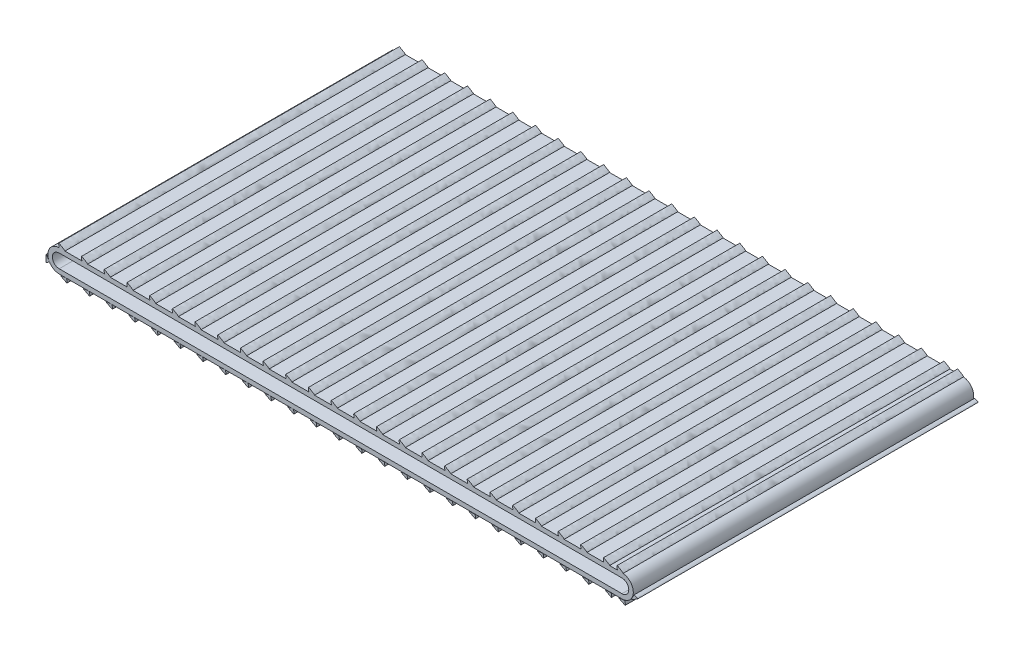
SolidWorks part; units mm, degrees
ref_plane "Front Plane" through (0, 0, 0) normal (0, 0, 1) x (1, 0, 0)
ref_plane "Top Plane" through (0, 0, 0) normal (0, 1, 0) x (1, 0, 0)
ref_plane "Right Plane" through (0, 0, 0) normal (1, 0, 0) x (0, 0, -1)
sketch "Sketch1" plane through (0, 0, 0) normal (0, 0, 1) x (1, 0, 0)
  line L0 (0, 40) -> (1240, 40)
  line L1 (0, 0) -> (1240, 0)
  line L3 (0, 50) -> (1240, 50)
  line L5 (0, 10) -> (1240, 10)
  arc A0 (1240, 50) -> (1240, 0) centre (1240, 25) cw
  arc A1 (0, 50) -> (0, 0) centre (0, 25) ccw
  arc A2 (1240, 40) -> (1240, 10) centre (1240, 25) cw
  arc A3 (0, 40) -> (0, 10) centre (0, 25) ccw
  dimension "D1" = 50
  dimension "D2" = 1240
  dimension "D3" = 10
extrude "Boss-Extrude1" add sketch "Sketch1" along normal blind 750
sketch "Sketch3" plane through (0, 0, 0) normal (0, 0, 1) x (1, 0, 0)
  line L0 (1240, 50) -> (0, 50) construction
  line L1 (7.4471, 50) -> (0, 50)
  line L2 (7.4471, 50) -> (12.5678, 50)
  line L3 (57.4471, 50) -> (62.5678, 50)
  line L4 (57.4471, 50) -> (50, 50)
  line L5 (107.4471, 50) -> (112.5678, 50)
  line L6 (107.4471, 50) -> (100, 50)
  line L7 (157.4471, 50) -> (162.5678, 50)
  line L8 (157.4471, 50) -> (150, 50)
  line L9 (207.4471, 50) -> (212.5678, 50)
  line L10 (207.4471, 50) -> (200, 50)
  line L11 (257.4471, 50) -> (262.5678, 50)
  line L12 (257.4471, 50) -> (250, 50)
  line L13 (307.4471, 50) -> (312.5678, 50)
  line L14 (307.4471, 50) -> (300, 50)
  line L15 (357.4471, 50) -> (362.5678, 50)
  line L16 (357.4471, 50) -> (350, 50)
  line L17 (407.4471, 50) -> (412.5678, 50)
  line L18 (407.4471, 50) -> (400, 50)
  line L19 (457.4471, 50) -> (462.5678, 50)
  line L20 (457.4471, 50) -> (450, 50)
  line L21 (507.4471, 50) -> (512.5678, 50)
  line L22 (507.4471, 50) -> (500, 50)
  line L23 (557.4471, 50) -> (562.5678, 50)
  line L24 (557.4471, 50) -> (550, 50)
  line L25 (607.4471, 50) -> (612.5678, 50)
  line L26 (607.4471, 50) -> (600, 50)
  line L27 (657.4471, 50) -> (662.5678, 50)
  line L28 (657.4471, 50) -> (650, 50)
  line L29 (707.4471, 50) -> (712.5678, 50)
  line L30 (707.4471, 50) -> (700, 50)
  line L31 (757.4471, 50) -> (762.5678, 50)
  line L32 (757.4471, 50) -> (750, 50)
  line L33 (807.4471, 50) -> (812.5678, 50)
  line L34 (807.4471, 50) -> (800, 50)
  line L35 (857.4471, 50) -> (862.5678, 50)
  line L36 (857.4471, 50) -> (850, 50)
  line L37 (907.4471, 50) -> (912.5678, 50)
  line L38 (907.4471, 50) -> (900, 50)
  line L39 (957.4471, 50) -> (962.5678, 50)
  line L40 (957.4471, 50) -> (950, 50)
  line L41 (1007.4471, 50) -> (1012.5678, 50)
  line L42 (1007.4471, 50) -> (1000, 50)
  line L43 (1057.4471, 50) -> (1062.5678, 50)
  line L44 (1057.4471, 50) -> (1050, 50)
  line L45 (1107.4471, 50) -> (1112.5678, 50)
  line L46 (1107.4471, 50) -> (1100, 50)
  line L47 (1157.4471, 50) -> (1162.5678, 50)
  line L48 (1157.4471, 50) -> (1150, 50)
  line L49 (1207.4471, 50) -> (1212.5678, 50)
  line L50 (1207.4471, 50) -> (1200, 50)
  line L55 (-25.3742, 18.9494) -> (-27.9345, 23.384)
  line L56 (-25.3742, 18.9494) -> (-21.6506, 12.5)
  line L57 (0, 25) -> (0, 50) construction
  line L58 (0, 25) -> (21.6506, 12.5) construction
  line L59 (17.9271, 6.0506) -> (21.6506, 12.5) [skipped]
  line L60 (17.9271, 6.0506) -> (15.3667, 1.616) [skipped]
  line L61 (1263.0971, 14.7108) -> (1260.5368, 10.2762)
  line L62 (1263.0971, 14.7108) -> (1266.8207, 21.1603)
  line L65 (1237.4471, 50) -> (1242.5678, 50)
  line L66 (1237.4471, 50) -> (1230, 50)
  line L69 (1208.6627, -0.6282) -> (1203.5497, -0.907)
  line L70 (1208.6627, -0.6282) -> (1216.0988, -0.2226)
  line L71 (1158.6627, -0.6282) -> (1153.5497, -0.907)
  line L72 (1158.6627, -0.6282) -> (1166.0988, -0.2226)
  line L73 (1108.6627, -0.6282) -> (1103.5497, -0.907)
  line L74 (1108.6627, -0.6282) -> (1116.0988, -0.2226)
  line L75 (1058.6627, -0.6282) -> (1053.5497, -0.907)
  line L76 (1058.6627, -0.6282) -> (1066.0988, -0.2226)
  line L77 (1008.6627, -0.6282) -> (1003.5497, -0.907)
  line L78 (1008.6627, -0.6282) -> (1016.0988, -0.2226)
  line L79 (958.6627, -0.6282) -> (953.5497, -0.907)
  line L80 (958.6627, -0.6282) -> (966.0988, -0.2226)
  line L81 (908.6627, -0.6282) -> (903.5497, -0.907)
  line L82 (908.6627, -0.6282) -> (916.0988, -0.2226)
  line L83 (858.6627, -0.6282) -> (853.5497, -0.907)
  line L84 (858.6627, -0.6282) -> (866.0988, -0.2226)
  line L85 (808.6627, -0.6282) -> (803.5497, -0.907)
  line L86 (808.6627, -0.6282) -> (816.0988, -0.2226)
  line L87 (758.6627, -0.6282) -> (753.5497, -0.907)
  line L88 (758.6627, -0.6282) -> (766.0988, -0.2226)
  line L89 (708.6627, -0.6282) -> (703.5497, -0.907)
  line L90 (708.6627, -0.6282) -> (716.0988, -0.2226)
  line L91 (658.6627, -0.6282) -> (653.5497, -0.907)
  line L92 (658.6627, -0.6282) -> (666.0988, -0.2226)
  line L93 (608.6627, -0.6282) -> (603.5497, -0.907)
  line L94 (608.6627, -0.6282) -> (616.0988, -0.2226)
  line L95 (558.6627, -0.6282) -> (553.5497, -0.907)
  line L96 (558.6627, -0.6282) -> (566.0988, -0.2226)
  line L97 (508.6627, -0.6282) -> (503.5497, -0.907)
  line L98 (508.6627, -0.6282) -> (516.0988, -0.2226)
  line L99 (458.6627, -0.6282) -> (453.5497, -0.907)
  line L100 (458.6627, -0.6282) -> (466.0988, -0.2226)
  line L101 (408.6627, -0.6282) -> (403.5497, -0.907)
  line L102 (408.6627, -0.6282) -> (416.0988, -0.2226)
  line L103 (358.6627, -0.6282) -> (353.5497, -0.907)
  line L104 (358.6627, -0.6282) -> (366.0988, -0.2226)
  line L105 (308.6627, -0.6282) -> (303.5497, -0.907)
  line L106 (308.6627, -0.6282) -> (316.0988, -0.2226)
  line L107 (258.6627, -0.6282) -> (253.5497, -0.907)
  line L108 (258.6627, -0.6282) -> (266.0988, -0.2226)
  line L109 (208.6627, -0.6282) -> (203.5497, -0.907)
  line L110 (208.6627, -0.6282) -> (216.0988, -0.2226)
  line L111 (158.6627, -0.6282) -> (153.5497, -0.907)
  line L112 (158.6627, -0.6282) -> (166.0988, -0.2226)
  line L113 (108.6627, -0.6282) -> (103.5497, -0.907)
  line L114 (108.6627, -0.6282) -> (116.0988, -0.2226)
  line L115 (58.6627, -0.6282) -> (53.5497, -0.907)
  line L116 (58.6627, -0.6282) -> (66.0988, -0.2226)
  line L117 (8.6627, -0.6282) -> (3.5497, -0.907)
  line L118 (8.6627, -0.6282) -> (16.0988, -0.2226)
  line L123 (1257.4471, 50) -> (1262.5678, 50) [skipped]
  line L124 (1257.4471, 50) -> (1250, 50) [skipped]
  line L125 (1238.6627, -0.6282) -> (1233.5497, -0.907)
  line L126 (1238.6627, -0.6282) -> (1246.0988, -0.2226)
  spline S0 degree 3 poles (0, 50) (-0.9028, 54.4851) (-2.0698, 60.2829) (5.1517, 55.1102) (14.2894, 50.7683) (12.5678, 50) knots 0 0 0 0 0.295978 0.3826 0.822655 0.822655 0.822655 0.822655
  spline S1 degree 3 poles (50, 50) (49.0972, 54.4851) (47.9302, 60.2829) (55.1517, 55.1102) (64.2894, 50.7683) (62.5678, 50) knots 0 0 0 0 0.295978 0.3826 0.822655 0.822655 0.822655 0.822655
  spline S2 degree 3 poles (100, 50) (99.0972, 54.4851) (97.9302, 60.2829) (105.1517, 55.1102) (114.2894, 50.7683) (112.5678, 50) knots 0 0 0 0 0.295978 0.3826 0.822655 0.822655 0.822655 0.822655
  spline S3 degree 3 poles (150, 50) (149.0972, 54.4851) (147.9302, 60.2829) (155.1517, 55.1102) (164.2894, 50.7683) (162.5678, 50) knots 0 0 0 0 0.295978 0.3826 0.822655 0.822655 0.822655 0.822655
  spline S4 degree 3 poles (200, 50) (199.0972, 54.4851) (197.9302, 60.2829) (205.1517, 55.1102) (214.2894, 50.7683) (212.5678, 50) knots 0 0 0 0 0.295978 0.3826 0.822655 0.822655 0.822655 0.822655
  spline S5 degree 3 poles (250, 50) (249.0972, 54.4851) (247.9302, 60.2829) (255.1517, 55.1102) (264.2894, 50.7683) (262.5678, 50) knots 0 0 0 0 0.295978 0.3826 0.822655 0.822655 0.822655 0.822655
  spline S6 degree 3 poles (300, 50) (299.0972, 54.4851) (297.9302, 60.2829) (305.1517, 55.1102) (314.2894, 50.7683) (312.5678, 50) knots 0 0 0 0 0.295978 0.3826 0.822655 0.822655 0.822655 0.822655
  spline S7 degree 3 poles (350, 50) (349.0972, 54.4851) (347.9302, 60.2829) (355.1517, 55.1102) (364.2894, 50.7683) (362.5678, 50) knots 0 0 0 0 0.295978 0.3826 0.822655 0.822655 0.822655 0.822655
  spline S8 degree 3 poles (400, 50) (399.0972, 54.4851) (397.9302, 60.2829) (405.1517, 55.1102) (414.2894, 50.7683) (412.5678, 50) knots 0 0 0 0 0.295978 0.3826 0.822655 0.822655 0.822655 0.822655
  spline S9 degree 3 poles (450, 50) (449.0972, 54.4851) (447.9302, 60.2829) (455.1517, 55.1102) (464.2894, 50.7683) (462.5678, 50) knots 0 0 0 0 0.295978 0.3826 0.822655 0.822655 0.822655 0.822655
  spline S10 degree 3 poles (500, 50) (499.0972, 54.4851) (497.9302, 60.2829) (505.1517, 55.1102) (514.2894, 50.7683) (512.5678, 50) knots 0 0 0 0 0.295978 0.3826 0.822655 0.822655 0.822655 0.822655
  spline S11 degree 3 poles (550, 50) (549.0972, 54.4851) (547.9302, 60.2829) (555.1517, 55.1102) (564.2894, 50.7683) (562.5678, 50) knots 0 0 0 0 0.295978 0.3826 0.822655 0.822655 0.822655 0.822655
  spline S12 degree 3 poles (600, 50) (599.0972, 54.4851) (597.9302, 60.2829) (605.1517, 55.1102) (614.2894, 50.7683) (612.5678, 50) knots 0 0 0 0 0.295978 0.3826 0.822655 0.822655 0.822655 0.822655
  spline S13 degree 3 poles (650, 50) (649.0972, 54.4851) (647.9302, 60.2829) (655.1517, 55.1102) (664.2894, 50.7683) (662.5678, 50) knots 0 0 0 0 0.295978 0.3826 0.822655 0.822655 0.822655 0.822655
  spline S14 degree 3 poles (700, 50) (699.0972, 54.4851) (697.9302, 60.2829) (705.1517, 55.1102) (714.2894, 50.7683) (712.5678, 50) knots 0 0 0 0 0.295978 0.3826 0.822655 0.822655 0.822655 0.822655
  spline S15 degree 3 poles (750, 50) (749.0972, 54.4851) (747.9302, 60.2829) (755.1517, 55.1102) (764.2894, 50.7683) (762.5678, 50) knots 0 0 0 0 0.295978 0.3826 0.822655 0.822655 0.822655 0.822655
  spline S16 degree 3 poles (800, 50) (799.0972, 54.4851) (797.9302, 60.2829) (805.1517, 55.1102) (814.2894, 50.7683) (812.5678, 50) knots 0 0 0 0 0.295978 0.3826 0.822655 0.822655 0.822655 0.822655
  spline S17 degree 3 poles (850, 50) (849.0972, 54.4851) (847.9302, 60.2829) (855.1517, 55.1102) (864.2894, 50.7683) (862.5678, 50) knots 0 0 0 0 0.295978 0.3826 0.822655 0.822655 0.822655 0.822655
  spline S18 degree 3 poles (900, 50) (899.0972, 54.4851) (897.9302, 60.2829) (905.1517, 55.1102) (914.2894, 50.7683) (912.5678, 50) knots 0 0 0 0 0.295978 0.3826 0.822655 0.822655 0.822655 0.822655
  spline S19 degree 3 poles (950, 50) (949.0972, 54.4851) (947.9302, 60.2829) (955.1517, 55.1102) (964.2894, 50.7683) (962.5678, 50) knots 0 0 0 0 0.295978 0.3826 0.822655 0.822655 0.822655 0.822655
  spline S20 degree 3 poles (1000, 50) (999.0972, 54.4851) (997.9302, 60.2829) (1005.1517, 55.1102) (1014.2894, 50.7683) (1012.5678, 50) knots 0 0 0 0 0.295978 0.3826 0.822655 0.822655 0.822655 0.822655
  spline S21 degree 3 poles (1050, 50) (1049.0972, 54.4851) (1047.9302, 60.2829) (1055.1517, 55.1102) (1064.2894, 50.7683) (1062.5678, 50) knots 0 0 0 0 0.295978 0.3826 0.822655 0.822655 0.822655 0.822655
  spline S22 degree 3 poles (1100, 50) (1099.0972, 54.4851) (1097.9302, 60.2829) (1105.1517, 55.1102) (1114.2894, 50.7683) (1112.5678, 50) knots 0 0 0 0 0.295978 0.3826 0.822655 0.822655 0.822655 0.822655
  spline S23 degree 3 poles (1150, 50) (1149.0972, 54.4851) (1147.9302, 60.2829) (1155.1517, 55.1102) (1164.2894, 50.7683) (1162.5678, 50) knots 0 0 0 0 0.295978 0.3826 0.822655 0.822655 0.822655 0.822655
  spline S24 degree 3 poles (1200, 50) (1199.0972, 54.4851) (1197.9302, 60.2829) (1205.1517, 55.1102) (1214.2894, 50.7683) (1212.5678, 50) knots 0 0 0 0 0.295978 0.3826 0.822655 0.822655 0.822655 0.822655
  spline S25 degree 3 poles (1230, 50) (1229.0972, 54.4851) (1227.9302, 60.2829) (1235.1517, 55.1102) (1244.2894, 50.7683) (1242.5678, 50) knots 0 0 0 0 0.295978 0.3826 0.822655 0.822655 0.822655 0.822655
  spline S26 degree 3 poles (1266.8207, 21.1603) (1271.1563, 19.6995) (1276.7609, 17.8112) (1268.6704, 14.1436) (1260.3414, 8.4012) (1260.5368, 10.2762) knots 0 0 0 0 0.295978 0.3826 0.822655 0.822655 0.822655 0.822655
  spline S27 degree 3 poles (-21.6506, 12.5) (-25.0835, 9.4756) (-29.521, 5.5661) (-28.6521, 14.4064) (-29.4607, 24.4908) (-27.9345, 23.384) knots 0 0 0 0 0.295978 0.3826 0.822655 0.822655 0.822655 0.822655
  spline S28 degree 3 poles (1246.0988, -0.2226) (1247.2444, -4.652) (1248.7254, -10.3776) (1241.233, -5.6058) (1231.8725, -1.7679) (1233.5497, -0.907) knots 0 0 0 0 0.295978 0.3826 0.822655 0.822655 0.822655 0.822655
  spline S29 degree 3 poles (1216.0988, -0.2226) (1217.2444, -4.652) (1218.7254, -10.3776) (1211.233, -5.6058) (1201.8725, -1.7679) (1203.5497, -0.907) knots 0 0 0 0 0.295978 0.3826 0.822655 0.822655 0.822655 0.822655
  spline S30 degree 3 poles (1166.0988, -0.2226) (1167.2444, -4.652) (1168.7254, -10.3776) (1161.233, -5.6058) (1151.8725, -1.7679) (1153.5497, -0.907) knots 0 0 0 0 0.295978 0.3826 0.822655 0.822655 0.822655 0.822655
  spline S31 degree 3 poles (1116.0988, -0.2226) (1117.2444, -4.652) (1118.7254, -10.3776) (1111.233, -5.6058) (1101.8725, -1.7679) (1103.5497, -0.907) knots 0 0 0 0 0.295978 0.3826 0.822655 0.822655 0.822655 0.822655
  spline S32 degree 3 poles (1066.0988, -0.2226) (1067.2444, -4.652) (1068.7254, -10.3776) (1061.233, -5.6058) (1051.8725, -1.7679) (1053.5497, -0.907) knots 0 0 0 0 0.295978 0.3826 0.822655 0.822655 0.822655 0.822655
  spline S33 degree 3 poles (1016.0988, -0.2226) (1017.2444, -4.652) (1018.7254, -10.3776) (1011.233, -5.6058) (1001.8725, -1.7679) (1003.5497, -0.907) knots 0 0 0 0 0.295978 0.3826 0.822655 0.822655 0.822655 0.822655
  spline S34 degree 3 poles (966.0988, -0.2226) (967.2444, -4.652) (968.7254, -10.3776) (961.233, -5.6058) (951.8725, -1.7679) (953.5497, -0.907) knots 0 0 0 0 0.295978 0.3826 0.822655 0.822655 0.822655 0.822655
  spline S35 degree 3 poles (916.0988, -0.2226) (917.2444, -4.652) (918.7254, -10.3776) (911.233, -5.6058) (901.8725, -1.7679) (903.5497, -0.907) knots 0 0 0 0 0.295978 0.3826 0.822655 0.822655 0.822655 0.822655
  spline S36 degree 3 poles (866.0988, -0.2226) (867.2444, -4.652) (868.7254, -10.3776) (861.233, -5.6058) (851.8725, -1.7679) (853.5497, -0.907) knots 0 0 0 0 0.295978 0.3826 0.822655 0.822655 0.822655 0.822655
  spline S37 degree 3 poles (816.0988, -0.2226) (817.2444, -4.652) (818.7254, -10.3776) (811.233, -5.6058) (801.8725, -1.7679) (803.5497, -0.907) knots 0 0 0 0 0.295978 0.3826 0.822655 0.822655 0.822655 0.822655
  spline S38 degree 3 poles (766.0988, -0.2226) (767.2444, -4.652) (768.7254, -10.3776) (761.233, -5.6058) (751.8725, -1.7679) (753.5497, -0.907) knots 0 0 0 0 0.295978 0.3826 0.822655 0.822655 0.822655 0.822655
  spline S39 degree 3 poles (716.0988, -0.2226) (717.2444, -4.652) (718.7254, -10.3776) (711.233, -5.6058) (701.8725, -1.7679) (703.5497, -0.907) knots 0 0 0 0 0.295978 0.3826 0.822655 0.822655 0.822655 0.822655
  spline S40 degree 3 poles (666.0988, -0.2226) (667.2444, -4.652) (668.7254, -10.3776) (661.233, -5.6058) (651.8725, -1.7679) (653.5497, -0.907) knots 0 0 0 0 0.295978 0.3826 0.822655 0.822655 0.822655 0.822655
  spline S41 degree 3 poles (616.0988, -0.2226) (617.2444, -4.652) (618.7254, -10.3776) (611.233, -5.6058) (601.8725, -1.7679) (603.5497, -0.907) knots 0 0 0 0 0.295978 0.3826 0.822655 0.822655 0.822655 0.822655
  spline S42 degree 3 poles (566.0988, -0.2226) (567.2444, -4.652) (568.7254, -10.3776) (561.233, -5.6058) (551.8725, -1.7679) (553.5497, -0.907) knots 0 0 0 0 0.295978 0.3826 0.822655 0.822655 0.822655 0.822655
  spline S43 degree 3 poles (516.0988, -0.2226) (517.2444, -4.652) (518.7254, -10.3776) (511.233, -5.6058) (501.8725, -1.7679) (503.5497, -0.907) knots 0 0 0 0 0.295978 0.3826 0.822655 0.822655 0.822655 0.822655
  spline S44 degree 3 poles (466.0988, -0.2226) (467.2444, -4.652) (468.7254, -10.3776) (461.233, -5.6058) (451.8725, -1.7679) (453.5497, -0.907) knots 0 0 0 0 0.295978 0.3826 0.822655 0.822655 0.822655 0.822655
  spline S45 degree 3 poles (416.0988, -0.2226) (417.2444, -4.652) (418.7254, -10.3776) (411.233, -5.6058) (401.8725, -1.7679) (403.5497, -0.907) knots 0 0 0 0 0.295978 0.3826 0.822655 0.822655 0.822655 0.822655
  spline S46 degree 3 poles (366.0988, -0.2226) (367.2444, -4.652) (368.7254, -10.3776) (361.233, -5.6058) (351.8725, -1.7679) (353.5497, -0.907) knots 0 0 0 0 0.295978 0.3826 0.822655 0.822655 0.822655 0.822655
  spline S47 degree 3 poles (316.0988, -0.2226) (317.2444, -4.652) (318.7254, -10.3776) (311.233, -5.6058) (301.8725, -1.7679) (303.5497, -0.907) knots 0 0 0 0 0.295978 0.3826 0.822655 0.822655 0.822655 0.822655
  spline S48 degree 3 poles (266.0988, -0.2226) (267.2444, -4.652) (268.7254, -10.3776) (261.233, -5.6058) (251.8725, -1.7679) (253.5497, -0.907) knots 0 0 0 0 0.295978 0.3826 0.822655 0.822655 0.822655 0.822655
  spline S49 degree 3 poles (216.0988, -0.2226) (217.2444, -4.652) (218.7254, -10.3776) (211.233, -5.6058) (201.8725, -1.7679) (203.5497, -0.907) knots 0 0 0 0 0.295978 0.3826 0.822655 0.822655 0.822655 0.822655
  spline S50 degree 3 poles (166.0988, -0.2226) (167.2444, -4.652) (168.7254, -10.3776) (161.233, -5.6058) (151.8725, -1.7679) (153.5497, -0.907) knots 0 0 0 0 0.295978 0.3826 0.822655 0.822655 0.822655 0.822655
  spline S51 degree 3 poles (116.0988, -0.2226) (117.2444, -4.652) (118.7254, -10.3776) (111.233, -5.6058) (101.8725, -1.7679) (103.5497, -0.907) knots 0 0 0 0 0.295978 0.3826 0.822655 0.822655 0.822655 0.822655
  spline S52 degree 3 poles (66.0988, -0.2226) (67.2444, -4.652) (68.7254, -10.3776) (61.233, -5.6058) (51.8725, -1.7679) (53.5497, -0.907) knots 0 0 0 0 0.295978 0.3826 0.822655 0.822655 0.822655 0.822655
  spline S53 degree 3 poles (16.0988, -0.2226) (17.2444, -4.652) (18.7254, -10.3776) (11.233, -5.6058) (1.8725, -1.7679) (3.5497, -0.907) knots 0 0 0 0 0.295978 0.3826 0.822655 0.822655 0.822655 0.822655
  point P157 (1260, 25)
  dimension "D3" = 120
  dimension "D1" = 26
  dimension "D4" = 2
  dimension "D5" = 2
  dimension "D2" = 3
extrude "Boss-Extrude2" add sketch "Sketch3" along normal up to surface (750 mm away) up to face at (620, 25, 750)
